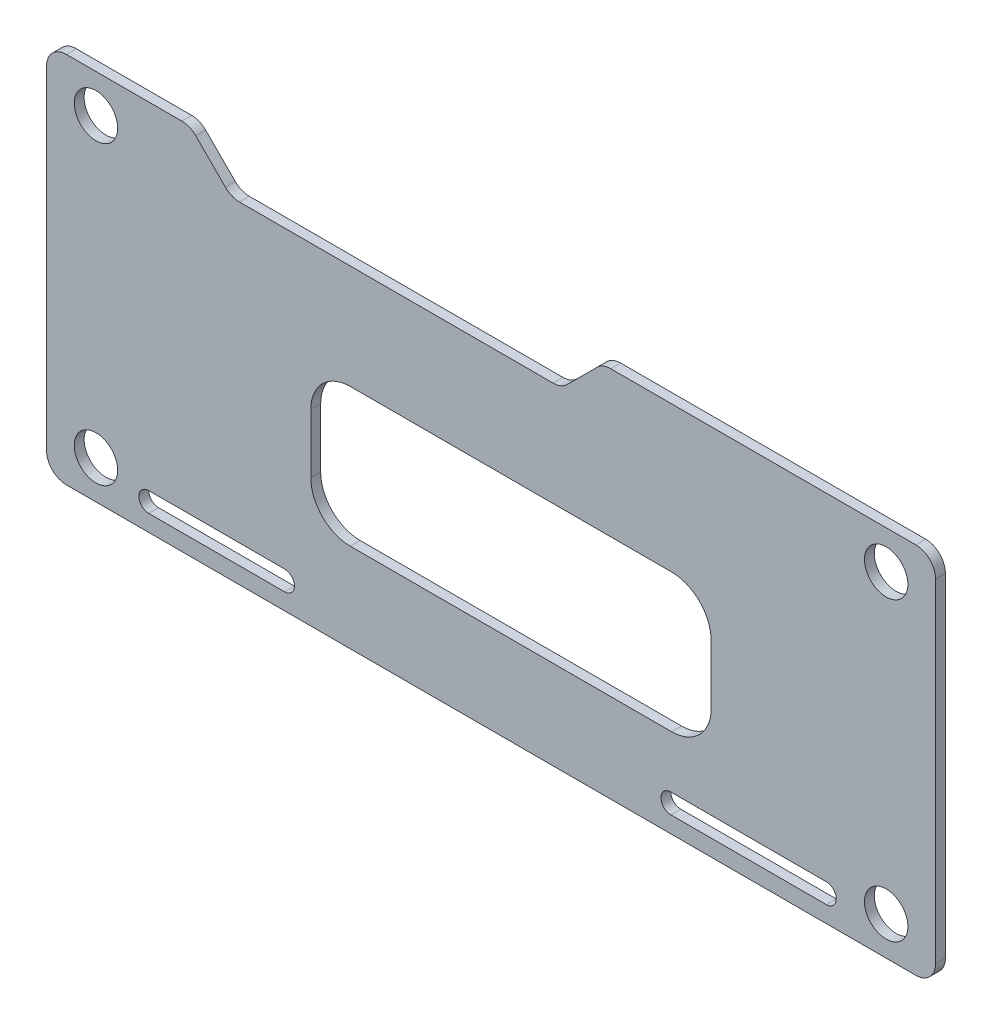
SolidWorks part; units mm, degrees
material "ABS"
ref_plane "前视基准面" through (0, 0, 0) normal (0, 0, 1) x (1, 0, 0)
ref_plane "上视基准面" through (0, 0, 0) normal (0, 1, 0) x (1, 0, 0)
ref_plane "右视基准面" through (0, 0, 0) normal (1, 0, 0) x (0, 0, -1)
sketch "草图1" plane through (0, 0, 0) normal (0, 0, 1) x (1, 0, 0)
  line L1 (-21.4884, 9.901) -> (18.5116, 9.901) construction
  line L2 (-21.4884, 9.901) -> (-21.4884, -5.099) construction
  line L3 (-21.4884, -5.099) -> (18.5116, -5.099) construction
  line L4 (18.5116, 9.901) -> (18.5116, -5.099) construction
  line L5 (-21.4884, 9.901) -> (18.5116, -5.099) construction
  line L6 (-21.4884, -5.099) -> (18.5116, 9.901) construction
  line L7 (-23.9884, 11.8368) -> (21.0116, 11.8368)
  line L8 (-23.9884, 11.8368) -> (-23.9884, -7.0348)
  line L9 (-23.9884, -7.0348) -> (21.0116, -7.0348)
  line L10 (21.0116, 11.8368) -> (21.0116, -7.0348)
  line L11 (-23.9884, 11.8368) -> (21.0116, -7.0348) construction
  line L12 (-23.9884, -7.0348) -> (21.0116, 11.8368) construction
  circle A0 centre (-21.4884, 9.901) radius 1.1
  circle A1 centre (-21.4884, -5.099) radius 1.1
  circle A2 centre (18.5116, -5.099) radius 1.1
  circle A3 centre (18.5116, 9.901) radius 1.1
  point P0 (-1.4884, 2.401)
  point P9 (-1.4884, 2.401)
  dimension "D3" = 45
  dimension "D1" = 15
  dimension "D2" = 40
extrude "凸台-拉伸1" add sketch "草图1" along normal blind 0.5
sketch "草图2" plane through (0, 0, 0.5) normal (0, 0, 1) x (1, 0, 0)
  line L0 (-16.7286, 11.8368) -> (-14.6398, 9.748)
  line L1 (21.0116, 11.8368) -> (-23.9884, 11.8368) construction
  line L2 (-14.6398, 9.748) -> (2.0715, 9.748)
  line L3 (2.0715, 9.748) -> (5.5197, 13.1963)
  line L4 (5.5197, 13.1963) -> (-14.8719, 13.1963)
  line L5 (-14.8719, 13.1963) -> (-16.7286, 11.8368)
  line L6 (-18.8159, -5.6988) -> (-11.9404, -5.6988) construction
  line L7 (-10.6138, 4.4657) -> (9.6518, 4.4657)
  line L8 (-10.6138, 4.4657) -> (-10.6138, -2.5364)
  line L9 (-10.6138, -2.5364) -> (9.6518, -2.5364)
  line L10 (9.6518, 4.4657) -> (9.6518, -2.5364)
  line L11 (-10.6138, 4.4657) -> (9.6518, -2.5364) construction
  line L12 (-10.6138, -2.5364) -> (9.6518, 4.4657) construction
  line L13 (-18.8159, -5.1988) -> (-11.9404, -5.1988)
  line L14 (-18.8159, -6.1988) -> (-11.9404, -6.1988)
  line L15 (7.6104, -5.6988) -> (15.4844, -5.6988) construction
  line L16 (7.6104, -5.1988) -> (15.4844, -5.1988)
  line L17 (7.6104, -6.1988) -> (15.4844, -6.1988)
  arc A0 (-18.8159, -5.1988) -> (-18.8159, -6.1988) centre (-18.8159, -5.6988) ccw
  arc A1 (-11.9404, -6.1988) -> (-11.9404, -5.1988) centre (-11.9404, -5.6988) ccw
  arc A2 (7.6104, -5.1988) -> (7.6104, -6.1988) centre (7.6104, -5.6988) ccw
  arc A3 (15.4844, -6.1988) -> (15.4844, -5.1988) centre (15.4844, -5.6988) ccw
  point P8 (-0.481, 0.9647)
  point P15 (-15.3781, -5.6988)
  point P20 (11.5474, -5.6988)
  dimension "D1" = 0.5
  dimension "D2" = 0.5
  dimension "D3" = 45
  dimension "D4" = 45
extrude "切除-拉伸1" cut sketch "草图2" against normal blind 1.5
fillet "圆角1" radius 1 4 edges at (4.1603, 11.8368, 0.25) (2.0715, 9.748, 0.25) (-14.6398, 9.748, 0.25) (-16.7286, 11.8368, 0.25)
fillet "圆角2" radius 1 4 edges at (21.0116, 11.8368, 0.25) (21.0116, -7.0348, 0.25) (-23.9884, -7.0348, 0.25) (-23.9884, 11.8368, 0.25)
fillet "圆角3" radius 2 4 edges at (9.6518, 4.4657, 0.25) (9.6518, -2.5364, 0.25) (-10.6138, -2.5364, 0.25) (-10.6138, 4.4657, 0.25)
